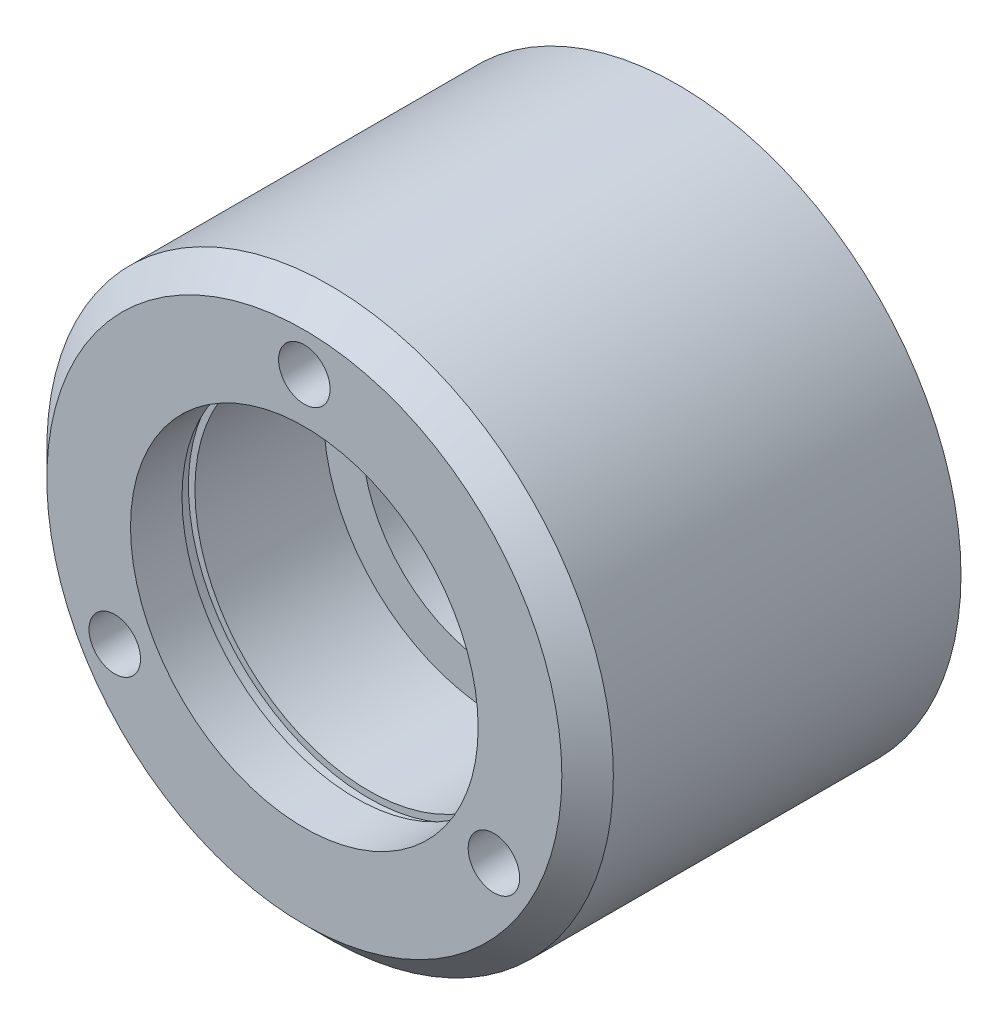
SolidWorks part; units mm, degrees
ref_plane "Plan de face" through (0, 0, 0) normal (0, 0, 1) x (1, 0, 0)
ref_plane "Plan de dessus" through (0, 0, 0) normal (0, 1, 0) x (1, 0, 0)
ref_plane "Plan de droite" through (0, 0, 0) normal (1, 0, 0) x (0, 0, -1)
sketch "Esquisse1" plane through (0, 0, 0) normal (0, 0, 1) x (1, 0, 0)
  circle A0 centre (0, 0) radius 11
  circle A1 centre (0, 0) radius 5.25
  dimension "D1" = 22
  dimension "D2" = 10.5
extrude "Boss.-Extru.1" add sketch "Esquisse1" along normal blind 7
sketch "Esquisse2" plane through (0, 0, 7) normal (0, 0, 1) x (1, 0, 0)
  circle A0 centre (0, 0) radius 11
  circle A1 centre (0, 0) radius 6.75
  dimension "D1" = 22
  dimension "D2" = 13.5
extrude "Boss.-Extru.2" add sketch "Esquisse2" along normal blind 5
sketch "Esquisse3" plane through (0, 0, 12) normal (0, 0, 1) x (1, 0, 0)
  circle A0 centre (0, 0) radius 7
  circle A1 centre (0, 0) radius 11
  dimension "D1" = 14
  dimension "D2" = 22
extrude "Boss.-Extru.3" add sketch "Esquisse3" along normal blind 0.5
sketch "Esquisse4" plane through (0, 0, 12.5) normal (0, 0, 1) x (1, 0, 0)
  circle A0 centre (0, 0) radius 6.75
  circle A1 centre (0, 0) radius 11
  dimension "D1" = 13.5
  dimension "D2" = 22
extrude "Boss.-Extru.4" add sketch "Esquisse4" along normal blind 2
cosmetic thread "Représentation de filetage2" parameters "D1"=14.5, "D2"=20.5
chamfer "Chanfrein1" distance 1 angle 45 1 edges at (11, 0, 14.5)
sketch "Esquisse7" plane through (0, 0, 0) normal (0, 0, -1) x (-1, 0, 0)
  line L0 (0, 0) -> (0, 8.5) construction
  line L4 (0, 0) -> (7.3612, -4.25) construction
  line L5 (0, 0) -> (-7.3612, -4.25) construction
  point P11 (0, 8.5)
  point P33 (0, 8.5)
  point P49 (7.3612, -4.25)
  point P50 (-7.3612, -4.25)
  dimension "D1" = 8.5
  dimension "D2" = 3
hole_wizard "Diamètre du perçage Ø2.0 (2)1" positions "Esquisse7" profile "Esquisse6" hole size "Ø2.0" standard "ISO" end condition through all
sketch "Esquisse6" plane through (7.3612, -4.25, 0) normal (1, 0, 0) x (0, 1, 0)
  line L0 (0, 0) -> (0, 14.5)
  line L1 (0, 14.5) -> (1, 14.5)
  line L2 (1, 14.5) -> (1, 0)
  line L5 (1, 0) -> (0, 0)
  line L11 (0, -6.35) -> (0, 107.95) construction
  dimension "Diamètre du perçage jusqu'au prochain" = 2
  dimension "Profondeur du perçage jusqu'au prochain" = 14.5
